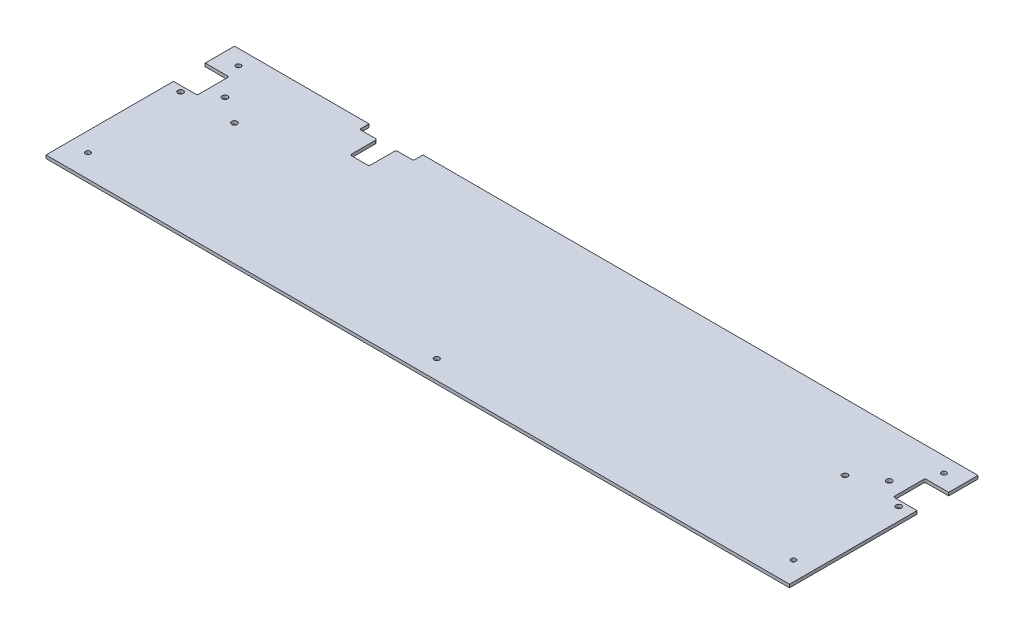
SolidWorks part; units mm, degrees
ref_plane "Alzado" through (0, 0, 0) normal (0, 0, 1) x (1, 0, 0)
ref_plane "Planta" through (0, 0, 0) normal (0, 1, 0) x (1, 0, 0)
ref_plane "Vista lateral" through (0, 0, 0) normal (1, 0, 0) x (0, 0, -1)
sketch "Croquis1" plane through (0, 0, 0) normal (0, 1, 0) x (1, 0, 0)
  line L0 (235.25, 120) -> (235.25, 0) construction
  line L1 (0, 0) -> (470.5, 0)
  line L2 (0, 0) -> (0, 120)
  line L3 (0, 120) -> (470.5, 120)
  line L4 (470.5, 0) -> (470.5, 120)
  line L5 (0, 60) -> (470.5, 60) construction
  circle A0 centre (12.5, 15) radius 1.55
  circle A1 centre (12.5, 110) radius 1.55
  circle A2 centre (458, 15) radius 1.55
  circle A3 centre (458, 110) radius 1.55
  dimension "D3" = 3.1
  dimension "D1" = 120
  dimension "D2" = 470.5
  dimension "D4" = 15
  dimension "D5" = 12.5
  dimension "D6" = 12.5
  dimension "D7" = 10
extrude "Saliente-Extruir1" add sketch "Croquis1" along normal blind 2
sketch "Croquis2" plane through (0, 0, 0) normal (0, -1, 0) x (1, 0, 0)
  line L0 (470, -0.5) -> (0.5, -0.5)
  line L1 (0.5, -0.5) -> (0.5, -119.5)
  line L2 (0.5, -119.5) -> (470, -119.5)
  line L3 (470, -119.5) -> (470, -0.5)
  line L4 (0, 0) -> (0, -120)
  line L5 (0, -120) -> (470.5, -120)
  line L6 (470.5, -120) -> (470.5, 0)
  line L7 (470.5, 0) -> (0, 0)
  line L8 (0, 0) -> (0, -120)
  line L9 (0, -120) -> (470.5, -120)
  line L10 (470.5, -120) -> (470.5, 0)
  line L11 (470.5, 0) -> (0, 0)
  dimension "D1" = 0
  dimension "D2" = 0.5
extrude "Cortar-Extruir1" cut sketch "Croquis2" against normal up to surface (2 mm away) up to face at (235.25, 2, -60)
sketch "Croquis3" plane through (0, 0, 0) normal (0, -1, 0) x (1, 0, 0)
  line L0 (0.5, -119.5) -> (470, -119.5) construction
  line L1 (85.5, -119.5) -> (119.5, -119.5)
  line L2 (85.5, -119.5) -> (85.5, -113.5)
  line L3 (85.5, -113.5) -> (96.5, -113.5)
  line L4 (119.5, -119.5) -> (119.5, -113.5)
  line L5 (108.5, -113.5) -> (119.5, -113.5)
  line L7 (96.5, -113.5) -> (96.5, -96.5)
  line L8 (96.5, -96.5) -> (108.5, -96.5)
  line L9 (108.5, -113.5) -> (108.5, -96.5)
  dimension "D1" = 34
  dimension "D2" = 6
  dimension "D3" = 12
  dimension "D4" = 85
  dimension "D5" = 17
  dimension "12" = 11
extrude "Cortar-Extruir2" cut sketch "Croquis3" against normal up to surface (2 mm away) up to face at (458, 2, -111.55)
fillet "Redondeo1" radius 1 6 edges at (85.5, 1, -113.5) (119.5, 1, -113.5) (108.5, 1, -113.5) (96.5, 1, -113.5) (96.5, 1, -96.5) (108.5, 1, -96.5)
sketch "Croquis4" plane through (0, 0, 0) normal (0, -1, 0) x (1, 0, 0)
  line L0 (235.25, -0.5) -> (235.25, -119.5) construction
  line L1 (470, -0.5) -> (0.5, -0.5) construction
  line L2 (119.5, -119.5) -> (470, -119.5) construction
  circle A0 centre (235.25, -12.5) radius 1.6
  dimension "D1" = 3.2
  dimension "D2" = 12
extrude "Cortar-Extruir3" cut sketch "Croquis4" against normal up to surface (2 mm away) up to face at (458, 2, -111.55)
sketch "Croquis5" plane through (0, 0, 0) normal (0, -1, 0) x (1, 0, 0)
  line L0 (235.25, -0.5) -> (235.25, -119.5) construction
  line L1 (470, -0.5) -> (0.5, -0.5) construction
  line L2 (119.5, -119.5) -> (470, -119.5) construction
  line L3 (0.5, -119.5) -> (85.5, -119.5) construction
  line L4 (0.5, -0.5) -> (0.5, -119.5) construction
  line L5 (470, -119.5) -> (470, -0.5) construction
  circle A0 centre (8.5, -77.5) radius 1.75
  circle A1 centre (42.5, -77.5) radius 1.75
  circle A2 centre (25.5, -88.5) radius 1.75
  circle A3 centre (462, -77.5) radius 1.75
  circle A4 centre (428, -77.5) radius 1.75
  circle A5 centre (445, -88.5) radius 1.75
  dimension "D1" = 3.5
  dimension "D2" = 42
  dimension "D3" = 8
  dimension "D4" = 8
  dimension "D5" = 42
  dimension "D6" = 34
  dimension "D7" = 34
  dimension "D8" = 11
  dimension "D9" = 17
  dimension "D10" = 17
  dimension "D11" = 11
extrude "Cortar-Extruir4" cut sketch "Croquis5" against normal up to surface (2 mm away) up to face at (235.25, 2, -14.1)
sketch "Croquis6" plane through (0, 0, 0) normal (0, -1, 0) x (1, 0, 0)
  line L0 (0.5, -0.5) -> (0.5, -119.5) construction
  line L1 (0.5, -81) -> (15.5, -81)
  line L2 (0.5, -81) -> (0.5, -101)
  line L3 (0.5, -101) -> (15.5, -101)
  line L4 (15.5, -81) -> (15.5, -101)
  line L5 (0.5, -119.5) -> (85.5, -119.5) construction
  line L6 (235.25, -0.5) -> (235.25, -119.5) construction
  line L7 (470, -0.5) -> (0.5, -0.5) construction
  line L8 (119.5, -119.5) -> (470, -119.5) construction
  line L9 (455, -81) -> (455, -101)
  line L10 (470, -101) -> (455, -101)
  line L11 (470, -81) -> (470, -101)
  line L12 (470, -81) -> (455, -81)
  dimension "D1" = 15
  dimension "D2" = 20
  dimension "D3" = 18.5
extrude "Cortar-Extruir5" cut sketch "Croquis6" against normal up to surface (2 mm away) up to face at (8.5, 2, -79.25)
fillet "Redondeo2" radius 1 4 edges at (455, 1, -101) (455, 1, -81) (15.5, 1, -101) (15.5, 1, -81)
